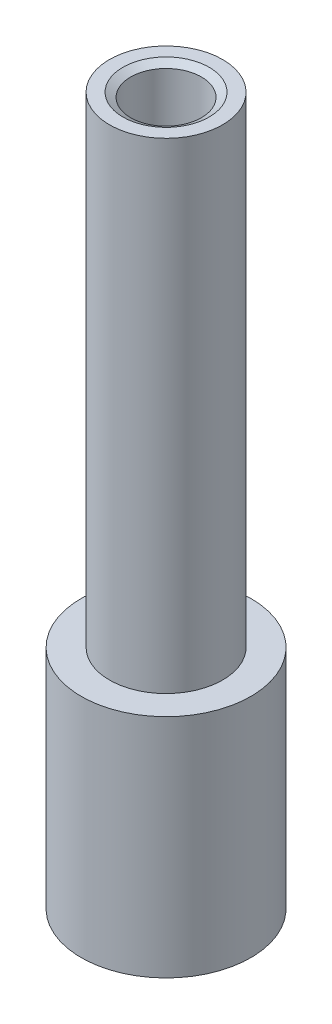
SolidWorks part; units mm, degrees
ref_plane "Спереди" through (0, 0, 0) normal (0, 0, 1) x (1, 0, 0)
ref_plane "Сверху" through (0, 0, 0) normal (0, 1, 0) x (1, 0, 0)
ref_plane "Справа" through (0, 0, 0) normal (1, 0, 0) x (0, 0, -1)
sketch "Эскиз2" plane through (0, 0, 0) normal (1, 0, 0) x (0, 0, -1)
  line L0 (0, 0) -> (0, 54.2669) construction
  line L1 (0, 0) -> (2, 0)
  line L2 (3, 0.01) -> (3, 8.01)
  line L3 (3, 8.01) -> (2, 8.01)
  line L4 (2, 8.01) -> (2, 25.01)
  line L5 (2, 25.01) -> (0, 25.01)
  line L6 (0, 0) -> (0, 25.01)
  line L7 (3, 0.01) -> (2, 0.01)
  line L8 (2, 0.01) -> (2, 0)
  dimension "D1" = 4
  dimension "D2" = 17
  dimension "D3" = 8.01
  dimension "D4" = 6
  dimension "D5" = 2
  dimension "D6" = 0.01
revolve "Повернуть1" add sketch "Эскиз2" angle 360 about L0
hole_wizard "Отверстие обработанное метчиком M32" positions "Эскиз4" profile "Эскиз3" tap size "M3" standard "DIN"
sketch "Эскиз4" plane through (0, 25.01, 0) normal (0, 1, 0) x (-1, 0, 0)
  point P0 (0, 0)
sketch "Эскиз3" plane through (0, 25.01, 0) normal (1, 0, 0) x (0, 0, 1)
  line L0 (0, 0) -> (0, 9.2511)
  line L1 (0, 9.2511) -> (1.25, 8.5)
  line L2 (1.25, 8.5) -> (1.25, 0.1588)
  line L3 (1.25, 0.1588) -> (1.525, 0)
  line L5 (1.525, 0) -> (0, 0)
  line L6 (-1.25, 0.1588) -> (-1.525, 0) construction
  line L10 (0, 9.2511) -> (-1.25, 8.5) construction
  line L11 (0, -6.35) -> (0, 107.95) construction
  dimension "Диаметр сверла" = 2.5
  dimension "Глубина сверла" = 8.5
  dimension "Диаметр передней зенковки" = 3.05
  dimension "Угол передней зенковки" = 120
  dimension "Угол заточки сверла" = 118
cosmetic thread "Отверстие резьбы1" parameters "D1"=6, "D2"=3
hole_wizard "Отверстие обработанное метчиком 1" positions "Эскиз6" profile "Эскиз5" tap size "M4" standard "DIN"
sketch "Эскиз6" plane through (0, 0, 0) normal (0, -1, 0) x (1, 0, 0)
  point P0 (0, 0)
sketch "Эскиз5" plane through (0, 0, 0) normal (1, 0, 0) x (0, 0, -1)
  line L0 (0, 0) -> (0, 6.9914)
  line L1 (0, 6.9914) -> (1.65, 6)
  line L2 (1.65, 6) -> (1.65, 0.2165)
  line L3 (1.65, 0.2165) -> (2.025, 0)
  line L5 (2.025, 0) -> (0, 0)
  line L6 (-1.65, 0.2165) -> (-2.025, 0) construction
  line L10 (0, 6.9914) -> (-1.65, 6) construction
  line L11 (0, -6.35) -> (0, 107.95) construction
  dimension "Диаметр сверла" = 3.3
  dimension "Глубина сверла" = 6
  dimension "Диаметр передней зенковки" = 4.05
  dimension "Угол передней зенковки" = 120
  dimension "Угол заточки сверла" = 118
cosmetic thread "Отверстие резьбы2" parameters "D1"=6, "D2"=4
